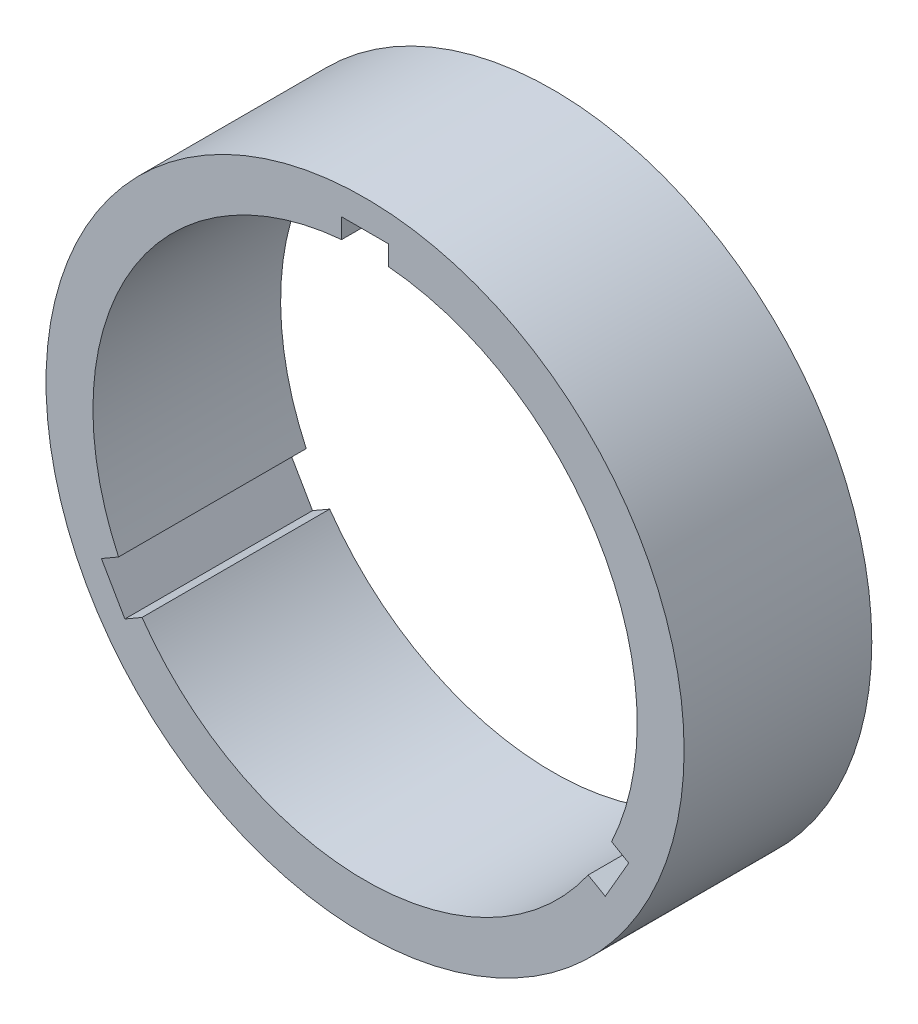
SolidWorks part; units mm, degrees
ref_plane "Alzado" through (0, 0, 0) normal (0, 0, 1) x (1, 0, 0)
ref_plane "Planta" through (0, 0, 0) normal (0, 1, 0) x (1, 0, 0)
ref_plane "Vista lateral" through (0, 0, 0) normal (1, 0, 0) x (0, 0, -1)
sketch "Croquis1" plane through (0, 0, 0) normal (0, 0, 1) x (1, 0, 0)
  line L0 (0, 34) -> (0, 31)
  line L1 (-2.5, 31) -> (2.5, 31)
  line L2 (-2.5, 31) -> (-2.5, 28.892)
  line L3 (2.5, 31) -> (2.5, 28.892)
  line L4 (28.0968, -13.3349) -> (25.5968, -17.6651)
  line L5 (25.5968, -17.6651) -> (23.7712, -16.6111)
  line L6 (28.0968, -13.3349) -> (26.2712, -12.281)
  line L7 (-25.5968, -17.6651) -> (-28.0968, -13.3349)
  line L8 (-28.0968, -13.3349) -> (-26.2712, -12.281)
  line L9 (-25.5968, -17.6651) -> (-23.7712, -16.6111)
  circle A0 centre (0, 0) radius 34
  circle A1 centre (0, 0) radius 29
  point P8 (0, 31)
  point P22 (0, 0)
  dimension "D1" = 68
  dimension "D4" = 58
  dimension "D2" = 3
  dimension "D3" = 5
  dimension "D5" = 3
extrude "Saliente-Extruir1" add sketch "Croquis1" along normal blind 20
